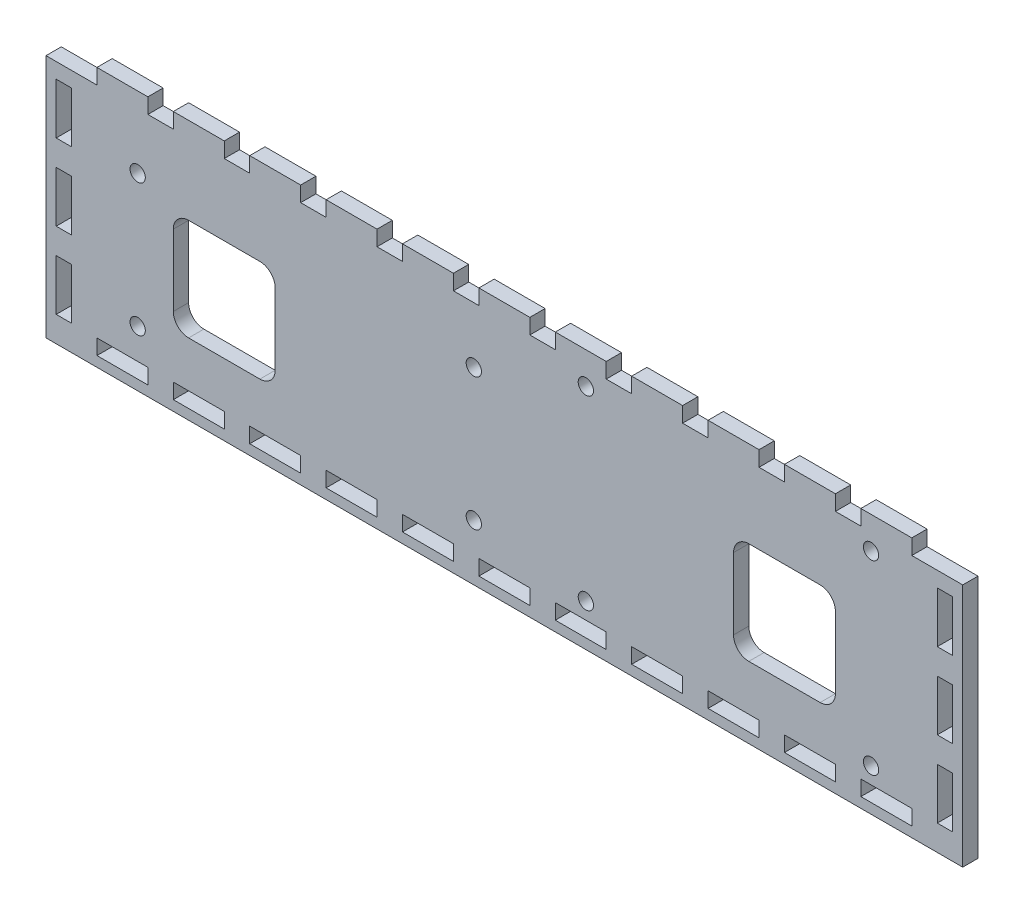
SolidWorks part; units mm, degrees
material "轻木"
ref_plane "前视基准面" through (0, 0, 0) normal (0, 0, 1) x (1, 0, 0)
ref_plane "上视基准面" through (0, 0, 0) normal (0, 1, 0) x (1, 0, 0)
ref_plane "右视基准面" through (0, 0, 0) normal (1, 0, 0) x (0, 0, -1)
sketch "草图1" plane through (0, 0, 0) normal (0, 0, 1) x (1, 0, 0)
  line L0 (-85, 6) -> (-85, -4)
  line L1 (-90, 24) -> (-80, 24)
  line L2 (-90, 24) -> (-90, -24)
  line L3 (-90, -24) -> (90, -24)
  line L4 (90, 24) -> (90, -24)
  line L5 (-90, 24) -> (90, -24) construction
  line L6 (-90, -24) -> (90, 24) construction
  line L7 (-85, 21) -> (-88, 21)
  line L8 (-85, 21) -> (-85, 11)
  line L9 (-85, 11) -> (-88, 11)
  line L10 (-88, 21) -> (-88, 11)
  line L11 (-85, 6) -> (-88, 6)
  line L12 (-88, 6) -> (-88, -4)
  line L13 (-85, -4) -> (-88, -4)
  line L14 (-85, -9) -> (-85, -19)
  line L15 (-85, -9) -> (-88, -9)
  line L16 (-88, -9) -> (-88, -19)
  line L17 (-85, -19) -> (-88, -19)
  line L18 (-65, 24) -> (-65, 27)
  line L20 (-80, 24) -> (-80, 27)
  line L21 (-80, 27) -> (-70, 27)
  line L22 (-70, 24) -> (-70, 27)
  line L24 (-55, 24) -> (-55, 27)
  line L25 (-65, 27) -> (-55, 27)
  line L26 (-50, 24) -> (-50, 27)
  line L28 (-40, 24) -> (-40, 27)
  line L29 (-50, 27) -> (-40, 27)
  line L30 (-35, 24) -> (-35, 27)
  line L32 (-25, 24) -> (-25, 27)
  line L33 (-35, 27) -> (-25, 27)
  line L34 (-20, 24) -> (-20, 27)
  line L36 (-10, 24) -> (-10, 27)
  line L37 (-20, 27) -> (-10, 27)
  line L38 (-5, 24) -> (-5, 27)
  line L40 (5, 24) -> (5, 27)
  line L41 (-5, 27) -> (5, 27)
  line L42 (10, 24) -> (10, 27)
  line L44 (20, 24) -> (20, 27)
  line L45 (10, 27) -> (20, 27)
  line L46 (25, 24) -> (25, 27)
  line L48 (35, 24) -> (35, 27)
  line L49 (25, 27) -> (35, 27)
  line L50 (40, 24) -> (40, 27)
  line L52 (50, 24) -> (50, 27)
  line L53 (40, 27) -> (50, 27)
  line L54 (55, 24) -> (55, 27)
  line L56 (65, 24) -> (65, 27)
  line L57 (55, 27) -> (65, 27)
  line L58 (70, 24) -> (70, 27)
  line L60 (80, 24) -> (80, 27)
  line L61 (70, 27) -> (80, 27)
  line L62 (0, -55) -> (0, 55) construction
  line L63 (85, -9) -> (88, -9)
  line L64 (88, -9) -> (88, -19)
  line L65 (85, -19) -> (88, -19)
  line L66 (85, -9) -> (85, -19)
  line L67 (85, 6) -> (88, 6)
  line L68 (88, 6) -> (88, -4)
  line L69 (85, -4) -> (88, -4)
  line L70 (85, 6) -> (85, -4)
  line L71 (85, 11) -> (88, 11)
  line L72 (88, 21) -> (88, 11)
  line L73 (85, 21) -> (88, 21)
  line L74 (85, 21) -> (85, 11)
  line L75 (-55, -22) -> (-55, -19)
  line L76 (-70, -22) -> (-80, -22)
  line L77 (-70, -22) -> (-70, -19)
  line L78 (-70, -19) -> (-80, -19)
  line L79 (-80, -22) -> (-80, -19)
  line L80 (-55, -22) -> (-65, -22)
  line L81 (-65, -22) -> (-65, -19)
  line L82 (-55, -19) -> (-65, -19)
  line L83 (-40, -22) -> (-40, -19)
  line L84 (-40, -22) -> (-50, -22)
  line L85 (-50, -22) -> (-50, -19)
  line L86 (-40, -19) -> (-50, -19)
  line L87 (-25, -22) -> (-25, -19)
  line L88 (-25, -22) -> (-35, -22)
  line L89 (-35, -22) -> (-35, -19)
  line L90 (-25, -19) -> (-35, -19)
  line L91 (-10, -22) -> (-10, -19)
  line L92 (-10, -22) -> (-20, -22)
  line L93 (-20, -22) -> (-20, -19)
  line L94 (-10, -19) -> (-20, -19)
  line L95 (5, -22) -> (5, -19)
  line L96 (5, -22) -> (-5, -22)
  line L97 (-5, -22) -> (-5, -19)
  line L98 (5, -19) -> (-5, -19)
  line L99 (20, -22) -> (20, -19)
  line L100 (20, -22) -> (10, -22)
  line L101 (10, -22) -> (10, -19)
  line L102 (20, -19) -> (10, -19)
  line L103 (35, -22) -> (35, -19)
  line L104 (35, -22) -> (25, -22)
  line L105 (25, -22) -> (25, -19)
  line L106 (35, -19) -> (25, -19)
  line L107 (50, -22) -> (50, -19)
  line L108 (50, -22) -> (40, -22)
  line L109 (40, -22) -> (40, -19)
  line L110 (50, -19) -> (40, -19)
  line L111 (65, -22) -> (65, -19)
  line L112 (65, -22) -> (55, -22)
  line L113 (55, -22) -> (55, -19)
  line L114 (65, -19) -> (55, -19)
  line L115 (80, -22) -> (80, -19)
  line L116 (80, -22) -> (70, -22)
  line L117 (70, -22) -> (70, -19)
  line L118 (80, -19) -> (70, -19)
  line L119 (-70, 24) -> (-65, 24)
  line L120 (-55, 24) -> (-50, 24)
  line L121 (-40, 24) -> (-35, 24)
  line L122 (-25, 24) -> (-20, 24)
  line L123 (-10, 24) -> (-5, 24)
  line L124 (5, 24) -> (10, 24)
  line L125 (20, 24) -> (25, 24)
  line L126 (35, 24) -> (40, 24)
  line L127 (50, 24) -> (55, 24)
  line L128 (65, 24) -> (70, 24)
  line L129 (80, 24) -> (90, 24)
  point P0 (0, 0)
  dimension "D1" = 48
  dimension "D2" = 180
  dimension "D3" = 10
  dimension "D4" = 3
  dimension "D5" = 3
  dimension "D6" = 2
  dimension "D8" = 10
  dimension "D9" = 3
  dimension "D10" = 10
  dimension "D11" = 10
  dimension "D13" = 3
  dimension "D14" = 2
  dimension "D15" = 10
  dimension "D7" = 3
  dimension "D12" = 11
  dimension "D16" = 11
extrude "凸台-拉伸1" add sketch "草图1" along normal blind 3
sketch "草图2" plane through (0, 0, 3) normal (0, 0, 1) x (1, 0, 0)
  line L0 (1.65, 0) -> (-1.65, 0) construction
  line L1 (45, 10) -> (65, 10)
  line L2 (45, 10) -> (45, -10)
  line L3 (45, -10) -> (65, -10)
  line L4 (65, 10) -> (65, -10)
  line L5 (45, 10) -> (65, -10) construction
  line L6 (45, -10) -> (65, 10) construction
  line L7 (85, 6) -> (85, -4) construction
  line L8 (0, -1.65) -> (0, 1.65) construction
  line L9 (-45, -10) -> (-65, -10)
  line L10 (-65, 10) -> (-65, -10)
  line L11 (-45, 10) -> (-65, 10)
  line L12 (-45, 10) -> (-45, -10)
  point P0 (55, 0)
  dimension "D1" = 20
  dimension "D2" = 20
  dimension "D3" = 30
extrude "切除-拉伸1" cut sketch "草图2" against normal blind 10
fillet "圆角1" radius 3 8 edges at (65, 10, 1.5) (65, -10, 1.5) (45, -10, 1.5) (45, 10, 1.5) (-45, 10, 1.5) (-45, -10, 1.5) (-65, -10, 1.5) (-65, 10, 1.5)
sketch "草图3" plane through (0, 0, 3) normal (0, 0, 1) x (1, 0, 0)
  line L0 (1.65, 0) -> (-1.65, 0) construction
  line L1 (-72, 13) -> (-6, 13) construction
  line L2 (-72, 13) -> (-72, -13) construction
  line L3 (-72, -13) -> (-6, -13) construction
  line L4 (-6, 13) -> (-6, -13) construction
  line L5 (-72, 13) -> (-6, -13) construction
  line L6 (-72, -13) -> (-6, 13) construction
  line L7 (40, 24) -> (35, 24) construction
  line L8 (16, 20.75) -> (72, 20.75) construction
  line L9 (16, 20.75) -> (16, -15.75) construction
  line L10 (16, -15.75) -> (72, -15.75) construction
  line L11 (72, 20.75) -> (72, -15.75) construction
  line L12 (16, 20.75) -> (72, -15.75) construction
  line L13 (16, -15.75) -> (72, 20.75) construction
  line L15 (-85, -4) -> (-85, 6) construction
  line L16 (85, 6) -> (85, -4) construction
  circle A0 centre (-72, 13) radius 1.5
  circle A1 centre (-6, 13) radius 1.5
  circle A2 centre (-72, -13) radius 1.5
  circle A3 centre (-6, -13) radius 1.5
  circle A4 centre (16, 20.75) radius 1.5
  circle A5 centre (16, -15.75) radius 1.5
  circle A6 centre (72, 20.75) radius 1.5
  circle A7 centre (72, -15.75) radius 1.5
  point P0 (-39, 0)
  point P7 (44, 2.5)
  dimension "D1" = 66
  dimension "D2" = 26
  dimension "D3" = 56
  dimension "D4" = 36.5
  dimension "D5" = 3.25
  dimension "D6" = 13
  dimension "D7" = 13
extrude "切除-拉伸2" cut sketch "草图3" against normal blind 10
